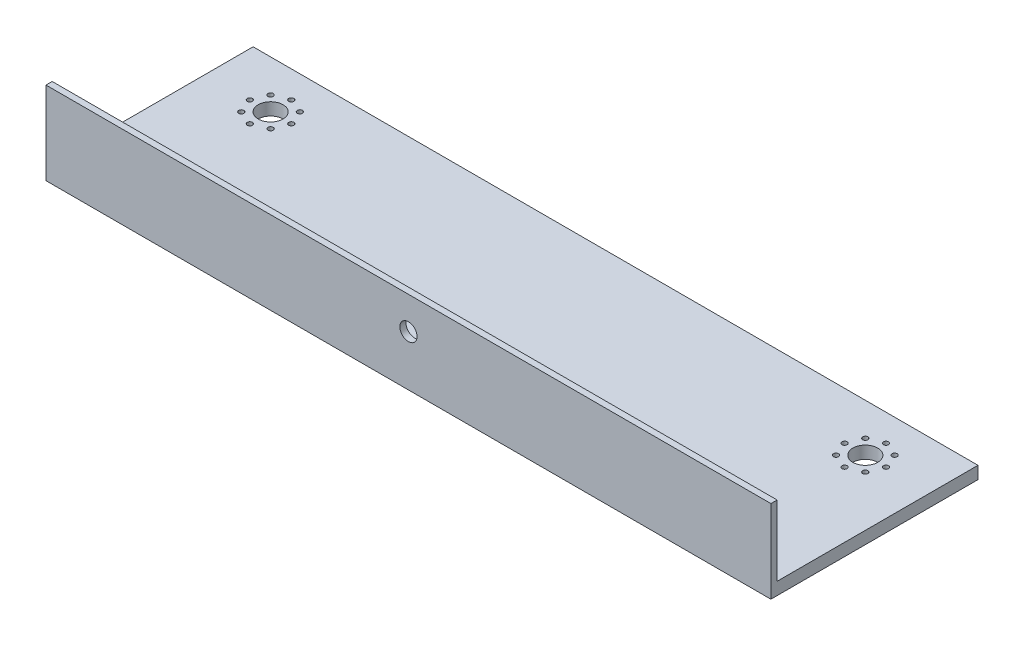
SolidWorks part; units mm, degrees
ref_plane "Front Plane" through (0, 0, 0) normal (0, 0, 1) x (1, 0, 0)
ref_plane "Top Plane" through (0, 0, 0) normal (0, 1, 0) x (1, 0, 0)
ref_plane "Right Plane" through (0, 0, 0) normal (1, 0, 0) x (0, 0, -1)
sketch "Sketch1" plane through (0, 0, 0) normal (0, 1, 0) x (1, 0, 0)
  line L0 (143.57, 45.6415) -> (143.57, -46.0508) construction
  line L1 (-175, -50) -> (175, -50)
  line L2 (-175, -50) -> (-175, 50)
  line L3 (-175, 50) -> (175, 50)
  line L4 (175, -50) -> (175, 50)
  line L5 (-175, -50) -> (175, 50) construction
  line L6 (-175, 50) -> (175, -50) construction
  line L7 (0, 45.6415) -> (0, -33.7706) construction
  line L8 (-143.57, 45.6415) -> (-143.57, -46.0508) construction
  circle A0 centre (143.57, 27.015) radius 6
  circle A1 centre (-143.57, 27.015) radius 6
  point P0 (0, 0)
  dimension "D4" = 12
  dimension "D5" = 12
  dimension "D1" = 100
  dimension "D2" = 350
  dimension "D3" = 143.57
extrude "Boss-Extrude1" add sketch "Sketch1" along normal mid plane 6
sketch "Sketch2" plane through (0, 0, 50) normal (0, 0, 1) x (1, 0, 0)
  line L0 (-175, 3) -> (-175, -3) construction
  line L1 (175, -3) -> (-175, -3)
  line L2 (175, -3) -> (175, 37)
  line L3 (175, 37) -> (-175, 37)
  line L4 (-175, -3) -> (-175, 37)
  line L5 (-175, 3) -> (-175, -3)
  dimension "D1" = 40
extrude "Boss-Extrude2" add sketch "Sketch2" against normal blind 3 contours L3 L4 L1 L2
sketch "Sketch3" plane through (0, 0, 50) normal (0, 0, 1) x (1, 0, 0)
  circle A0 centre (0, 21.3696) radius 4.15
  dimension "D1" = 8.3
extrude "Cut-Extrude1" cut sketch "Sketch3" against normal through all
sketch "Sketch4" plane through (0, 3, 0) normal (0, 1, 0) x (1, 0, 0)
  line L0 (143.57, 27.015) -> (143.57, 37.015) construction
  line L1 (143.57, 27.015) -> (136.4989, 34.0861) construction
  line L2 (143.57, 27.015) -> (139.0883, 27.015) construction
  circle A0 centre (143.57, 37.015) radius 1.25
  circle A1 centre (143.57, 27.015) radius 10 construction
  circle A2 centre (153.57, 27.015) radius 1.25
  circle A3 centre (143.57, 17.015) radius 1.25
  circle A4 centre (133.57, 27.015) radius 1.25
  circle A5 centre (136.4989, 34.0861) radius 1.25
  circle A6 centre (150.6411, 34.0861) radius 1.25
  circle A7 centre (150.6411, 19.944) radius 1.25
  circle A8 centre (136.4989, 19.944) radius 1.25
  dimension "D2" = 2.5
  dimension "D3" = 45
  dimension "D1" = 10
extrude "Cut-Extrude2" cut sketch "Sketch4" against normal through all
mirror "Mirror1" about plane through (0, 0, 0) normal (1, 0, 0) of "Cut-Extrude2"
